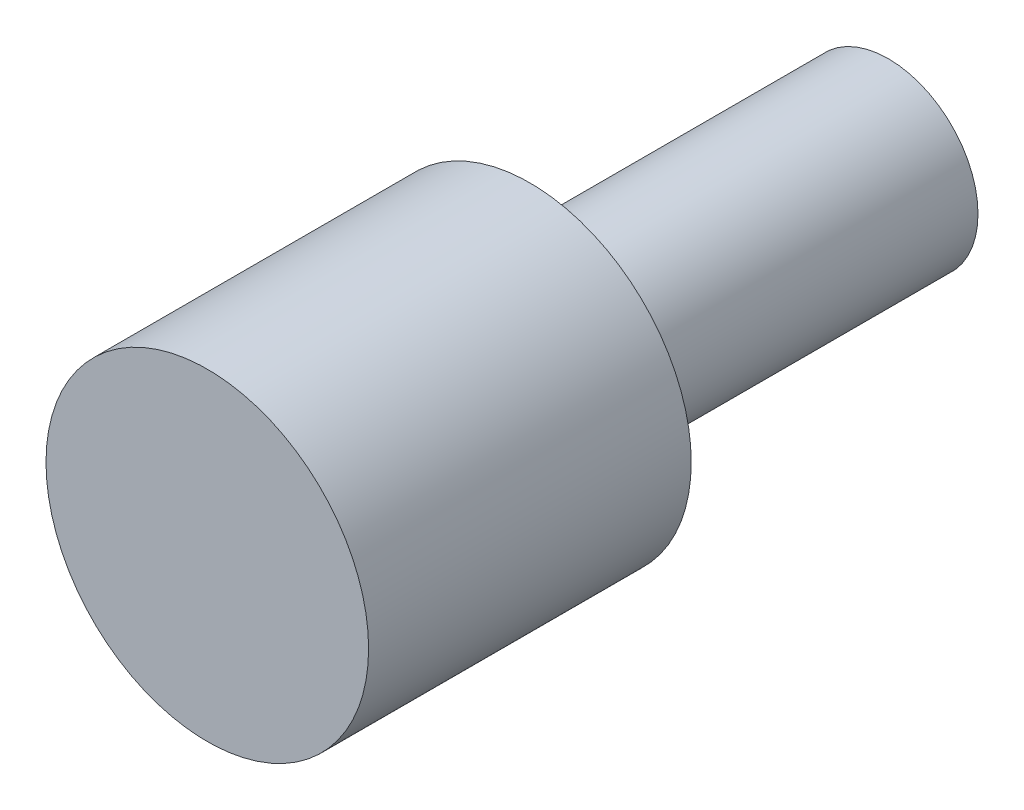
SolidWorks part; units mm, degrees
material "AISI 304"
ref_plane "Front" through (0, 0, 0) normal (0, 0, 1) x (1, 0, 0)
ref_plane "Top" through (0, 0, 0) normal (0, 1, 0) x (1, 0, 0)
ref_plane "Right" through (0, 0, 0) normal (1, 0, 0) x (0, 0, -1)
sketch "Sketch1" plane through (0, 0, 0) normal (0, 0, 1) x (1, 0, 0)
  circle A0 centre (0, 0) radius 2.5
  dimension "D1" = 5
extrude "Boss-Extrude1" add sketch "Sketch1" along normal blind 10
sketch "Sketch2" plane through (0, 0, 10) normal (0, 0, 1) x (1, 0, 0)
  circle A0 centre (0, 0) radius 4.5
  dimension "D1" = 9
extrude "Boss-Extrude2" add sketch "Sketch2" along normal blind 9
